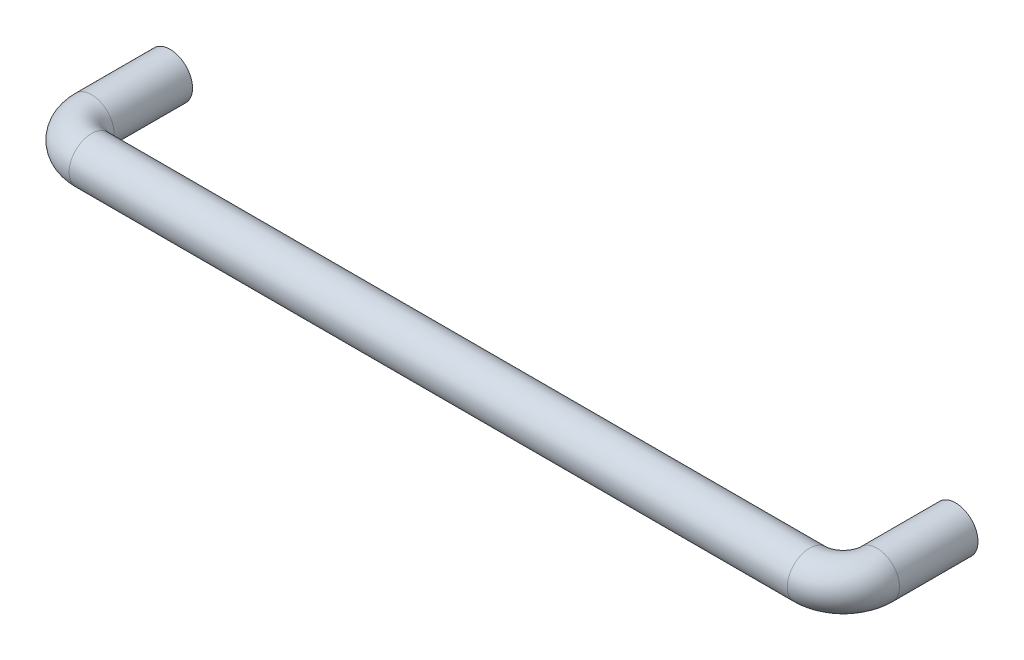
SolidWorks part; units mm, degrees
ref_plane "Front Plane" through (0, 0, 0) normal (0, 0, 1) x (1, 0, 0)
ref_plane "Top Plane" through (0, 0, 0) normal (0, 1, 0) x (1, 0, 0)
ref_plane "Right Plane" through (0, 0, 0) normal (1, 0, 0) x (0, 0, -1)
sketch "Sketch1" plane through (0, 0, 0) normal (0, 1, 0) x (1, 0, 0)
  line L0 (0, 0) -> (0, -3.5)
  line L1 (-1.5, -5) -> (-33.5, -5)
  line L2 (-35, -3.5) -> (-35, 0)
  arc A0 (-1.5, -5) -> (0, -3.5) centre (-1.5, -3.5) ccw
  arc A1 (-35, -3.5) -> (-33.5, -5) centre (-33.5, -3.5) ccw
  dimension "D1" = 3
  dimension "D5" = 3
  dimension "D2" = 3.5
  dimension "D3" = 35
sketch "Sketch2" plane through (0, 0, 0) normal (0, 0, 1) x (1, 0, 0)
  circle A0 centre (0, 0) radius 1
  dimension "D1" = 2
sweep "Sweep1" add profiles "Sketch2" path "Sketch1"
